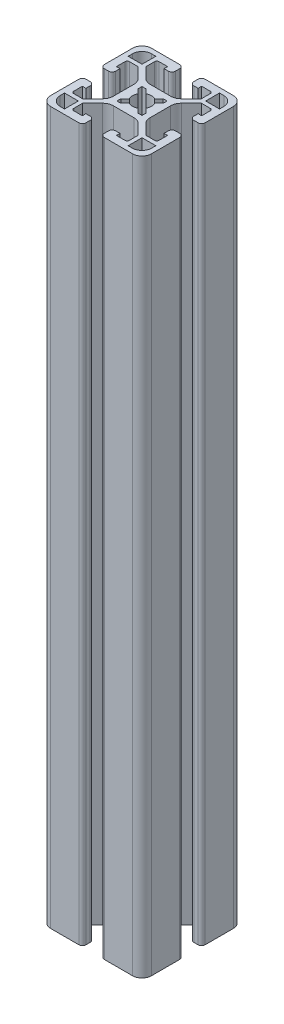
SolidWorks part; units mm, degrees
ref_plane "Front Plane" through (0, 0, 0) normal (0, 0, 1) x (1, 0, 0)
ref_plane "Top Plane" through (0, 0, 0) normal (0, 1, 0) x (1, 0, 0)
ref_plane "Right Plane" through (0, 0, 0) normal (1, 0, 0) x (0, 0, -1)
sketch "Sketch1" plane through (0, 0, 0) normal (0, 1, 0) x (1, 0, 0)
  line L0 (-7.366, -4.572) -> (7.366, -4.572) construction
  line L1 (-7.366, -7.366) -> (7.366, -7.366) construction
  line L2 (-7.366, -7.366) -> (-7.366, 7.366) construction
  line L3 (-7.366, 7.366) -> (7.366, 7.366) construction
  line L4 (7.366, -7.366) -> (7.366, 7.366) construction
  line L5 (-7.366, -7.366) -> (7.366, 7.366) construction
  line L6 (-7.366, 7.366) -> (7.366, -7.366) construction
  line L7 (-7.366, -5.6642) -> (7.366, -5.6642) construction
  line L8 (-7.366, -3.302) -> (7.366, -3.302) construction
  line L9 (-6.6835, -8.0485) -> (5.4041, 4.0391) construction
  line L10 (4.5109, 7.366) -> (4.5109, -7.366) construction
  line L11 (-7.366, -7.366) -> (7.366, -7.366)
  line L12 (7.366, -7.366) -> (7.366, -3.302)
  line L13 (0, 0) -> (0, -7.366) construction
  line L14 (-0.7239, -0.7239) -> (-0.7239, -7.366) construction
  line L15 (0.7239, -0.6411) -> (0.7239, -7.366) construction
  line L16 (7.366, -3.302) -> (4.5109, -3.302)
  line L17 (4.5109, -3.302) -> (4.572, -4.572)
  line L18 (4.572, -4.572) -> (0.7239, -4.572)
  line L19 (0.7239, -4.572) -> (0.7239, -0.6411)
  line L20 (0.7239, -0.6411) -> (5.4041, 4.0391)
  line L21 (-6.6835, -8.0485) -> (8.0485, 6.6835) construction
  line L22 (-5.6642, -5.6642) -> (-0.7239, -5.6642)
  line L23 (-0.7239, -5.6642) -> (-0.7239, -0.7239)
  line L24 (0.7239, 0) -> (0.7239, -7.366) construction
  line L25 (-0.7239, 0) -> (-0.7239, -7.366) construction
  line L26 (-7.366, -7.366) -> (10.6304, 10.6304) construction
  line L27 (-0.6411, 0.7239) -> (4.0391, 5.4041)
  line L28 (-7.366, 7.366) -> (-3.302, 7.366)
  line L29 (-3.302, 7.366) -> (-3.302, 4.5109)
  line L30 (-3.302, 4.5109) -> (-4.572, 4.572)
  line L31 (-4.572, 4.572) -> (-4.572, 0.7239)
  line L32 (-4.572, 0.7239) -> (-0.6411, 0.7239)
  line L33 (-5.6642, -0.7239) -> (-0.7239, -0.7239)
  line L34 (-5.6642, -5.6642) -> (-5.6642, -0.7239)
  line L35 (-7.366, -7.366) -> (-7.366, 7.366)
  line L36 (7.366, 24.5629) -> (4.5109, 24.5629)
  line L37 (7.366, 28.6269) -> (7.366, 24.5629)
  line L38 (-7.366, 28.6269) -> (7.366, 28.6269)
  line L39 (4.572, 25.8329) -> (0.7239, 25.8329)
  line L40 (4.5109, 24.5629) -> (4.572, 25.8329)
  line L41 (0.7239, 25.8329) -> (0.7239, 21.902)
  line L42 (0.7239, 21.902) -> (5.4041, 17.2217)
  line L43 (-0.7239, 26.9251) -> (-0.7239, 21.9848)
  line L44 (-5.6642, 26.9251) -> (-0.7239, 26.9251)
  line L45 (-5.6642, 26.9251) -> (-5.6642, 21.9848)
  line L46 (-5.6642, 21.9848) -> (-0.7239, 21.9848)
  line L47 (-7.366, 28.6269) -> (-7.366, 13.8949)
  line L48 (-4.572, 20.537) -> (-0.6411, 20.537)
  line L49 (-4.572, 16.6889) -> (-4.572, 20.537)
  line L50 (-3.302, 16.75) -> (-4.572, 16.6889)
  line L51 (-3.302, 13.8949) -> (-3.302, 16.75)
  line L52 (-7.366, 13.8949) -> (-3.302, 13.8949)
  line L53 (-0.6411, 20.537) -> (4.0391, 15.8567)
  line L54 (24.5629, 13.8949) -> (24.5629, 16.75)
  line L55 (28.6269, 13.8949) -> (24.5629, 13.8949)
  line L56 (28.6269, 28.6269) -> (28.6269, 13.8949)
  line L57 (25.8329, 16.6889) -> (25.8329, 20.537)
  line L58 (24.5629, 16.75) -> (25.8329, 16.6889)
  line L59 (25.8329, 20.537) -> (21.902, 20.537)
  line L60 (21.902, 20.537) -> (17.2217, 15.8567)
  line L61 (26.9251, 21.9848) -> (21.9848, 21.9848)
  line L62 (26.9251, 26.9251) -> (26.9251, 21.9848)
  line L63 (26.9251, 26.9251) -> (21.9848, 26.9251)
  line L64 (21.9848, 26.9251) -> (21.9848, 21.9848)
  line L65 (28.6269, 28.6269) -> (13.8949, 28.6269)
  line L66 (20.537, 25.8329) -> (20.537, 21.902)
  line L67 (16.6889, 25.8329) -> (20.537, 25.8329)
  line L68 (16.75, 24.5629) -> (16.6889, 25.8329)
  line L69 (13.8949, 24.5629) -> (16.75, 24.5629)
  line L70 (13.8949, 28.6269) -> (13.8949, 24.5629)
  line L71 (20.537, 21.902) -> (15.8567, 17.2217)
  line L72 (13.8949, -3.302) -> (16.75, -3.302)
  line L73 (13.8949, -7.366) -> (13.8949, -3.302)
  line L74 (28.6269, -7.366) -> (13.8949, -7.366)
  line L75 (16.6889, -4.572) -> (20.537, -4.572)
  line L76 (16.75, -3.302) -> (16.6889, -4.572)
  line L77 (20.537, -4.572) -> (20.537, -0.6411)
  line L78 (20.537, -0.6411) -> (15.8567, 4.0391)
  line L79 (21.9848, -5.6642) -> (21.9848, -0.7239)
  line L80 (26.9251, -5.6642) -> (21.9848, -5.6642)
  line L81 (26.9251, -5.6642) -> (26.9251, -0.7239)
  line L82 (26.9251, -0.7239) -> (21.9848, -0.7239)
  line L83 (28.6269, -7.366) -> (28.6269, 7.366)
  line L84 (25.8329, 0.7239) -> (21.902, 0.7239)
  line L85 (25.8329, 4.572) -> (25.8329, 0.7239)
  line L86 (24.5629, 4.5109) -> (25.8329, 4.572)
  line L87 (24.5629, 7.366) -> (24.5629, 4.5109)
  line L88 (28.6269, 7.366) -> (24.5629, 7.366)
  line L89 (21.902, 0.7239) -> (17.2217, 5.4041)
  line L90 (10.6304, 10.6304) -> (28.6269, 28.6269) construction
  line L91 (-7.366, 28.6269) -> (28.6269, -7.366) construction
  line L92 (6.1575, 13.7384) -> (13.7384, 6.1575) construction
  line L94 (4.0391, 5.4041) -> (4.0391, 15.8567)
  line L95 (5.4041, 17.2217) -> (15.8567, 17.2217)
  line L96 (17.2217, 5.4041) -> (17.2217, 15.8567)
  line L97 (4.0391, 4.0391) -> (17.2217, 17.2217) construction
  line L98 (4.0391, 17.2217) -> (17.2217, 4.0391) construction
  line L99 (7.5225, 15.1034) -> (15.1034, 7.5225) construction
  line L100 (13.7384, 15.1034) -> (6.1575, 7.5225) construction
  line L101 (15.1034, 13.7384) -> (7.5225, 6.1575) construction
  line L102 (5.4041, 4.0391) -> (15.8567, 4.0391)
  line L103 (7.6963, 12.1996) -> (6.1575, 13.7384)
  line L104 (6.1575, 6.1575) -> (6.1575, 7.5225)
  line L105 (6.1575, 15.1034) -> (7.5225, 15.1034)
  line L106 (5.4041, 15.1034) -> (15.8567, 15.1034) construction
  line L107 (6.1575, 5.4041) -> (6.1575, 15.8567) construction
  line L108 (7.5225, 15.1034) -> (9.0613, 13.5646)
  line L109 (13.7384, 15.1034) -> (15.1034, 15.1034)
  line L110 (6.1575, 13.7384) -> (6.1575, 15.1034)
  line L111 (15.1034, 6.1575) -> (15.1034, 7.5225)
  line L112 (6.1575, 6.1575) -> (7.5225, 6.1575)
  line L113 (13.7384, 15.1034) -> (12.1996, 13.5646)
  line L114 (13.5646, 12.1996) -> (15.1034, 13.7384)
  line L115 (12.1996, 7.6963) -> (13.7384, 6.1575)
  line L116 (13.5646, 9.0613) -> (15.1034, 7.5225)
  line L117 (9.0613, 7.6963) -> (7.5225, 6.1575)
  line L118 (7.6963, 9.0613) -> (6.1575, 7.5225)
  line L119 (13.7384, 6.1575) -> (15.1034, 6.1575)
  line L120 (15.1034, 13.7384) -> (15.1034, 15.1034)
  circle A0 centre (10.6304, 10.6304) radius 0.1397
  arc A1 (7.6963, 12.1996) -> (7.6963, 9.0613) centre (10.6304, 10.6304) ccw
  arc A2 (9.0613, 7.6963) -> (12.1996, 7.6963) centre (10.6304, 10.6304) ccw
  arc A3 (12.1996, 13.5646) -> (9.0613, 13.5646) centre (10.6304, 10.6304) ccw
  arc A4 (13.5646, 9.0613) -> (13.5646, 12.1996) centre (10.6304, 10.6304) ccw
  point P0 (0, 0)
  point P16 (4.5109, -3.302)
  point P17 (4.5109, -3.302)
  point P20 (4.572, -4.572)
  point P24 (-1.8093, -4.572)
  point P28 (0.7239, -4.572)
  point P29 (-0.7239, -5.6642)
  point P30 (0.7239, -0.6411)
  point P32 (-0.7239, -0.7239)
  point P33 (7.366, 6.001)
  point P37 (-5.6642, -5.6642)
  point P115 (9.0613, 13.5646)
  point P117 (10.6304, 10.6304)
  point P123 (7.6963, 12.1996)
  point P124 (12.1996, 13.5646)
  point P125 (9.0613, 7.6963)
  point P126 (13.5646, 12.1996)
  point P127 (13.5646, 9.0613)
  point P128 (12.1996, 7.6963)
  point P129 (7.6963, 9.0613)
  point P150 (6.1575, 6.1575)
  dimension "D14" = 6.6548
  dimension "D1" = 14.732
  dimension "D2" = 14.732
  dimension "D3" = 2.794
  dimension "D4" = 1.7018
  dimension "D5" = 4.064
  dimension "D7" = 2.8551
  dimension "D10" = 25.4508
  dimension "D12" = 13.1826
  dimension "D13" = 13.1826
  dimension "D16" = 2.1184
  dimension "D18" = 6.5913
  dimension "D19" = 6.5913
  dimension "D20" = 6.5913
  dimension "D21" = 90
  dimension "D22" = 1.9304
  dimension "D8" = 0.7239
  dimension "D9" = 0.7239
  dimension "D6" = 0.9652
  dimension "D15" = 2.1184
  dimension "D11" = 4
extrude "Boss-Extrude6" add sketch "Sketch1" along normal blind 254 contours L20 L102 L78 L77 L75 L76 L72 L73 L74 L83 L88 L87 L86 L85 L84 L89 L96 L60 L59 L57 L58 L54 L55 L56 L65 L70 L69 L68 L67 L66 L71 L95 L42 L41 L39 L40 L36 L37 L38 L47 L52 L51 L50 L49 L48 L53 L94 L27 L32 L31 L30
fillet "Fillet1" radius 3.4125 8 edges at (-7.366, 127, -28.6269) (26.9251, 127, -26.9251) (26.9251, 127, 5.6642) (-5.6642, 127, 5.6642) (28.6269, 127, 7.366) (28.6269, 127, -28.6269) (-5.6642, 127, -26.9251) (-7.366, 127, 7.366)
fillet "Fillet2" radius 0.762 8 edges at (25.8329, 127, -0.7239) (20.537, 127, 4.572) (0.7239, 127, 4.572) (-4.572, 127, -0.7239) (-4.572, 127, -20.537) (25.8329, 127, -20.537) (20.537, 127, -25.8329) (0.7239, 127, -25.8329)
fillet "Fillet3" radius 1.27 16 edges at (-7.366, 127, -13.8949) (-3.302, 127, -13.8949) (7.366, 127, -28.6269) (7.366, 127, -24.5629) (13.8949, 127, -24.5629) (13.8949, 127, -28.6269) (28.6269, 127, -13.8949) (24.5629, 127, -13.8949) (24.5629, 127, -7.366) (28.6269, 127, -7.366) (13.8949, 127, 7.366) (13.8949, 127, 3.302) (7.366, 127, 7.366) (7.366, 127, 3.302) (-7.366, 127, -7.366) (-3.302, 127, -7.366)
fillet "Fillet4" radius 3.81 8 edges at (15.8567, 127, -17.2217) (4.0391, 127, -15.8567) (4.0391, 127, -5.4041) (5.4041, 127, -4.0391) (15.8567, 127, -4.0391) (17.2217, 127, -5.4041) (17.2217, 127, -15.8567) (5.4041, 127, -17.2217)
equation "\"D2@Sketch1\"=\"D1@Sketch1\""
